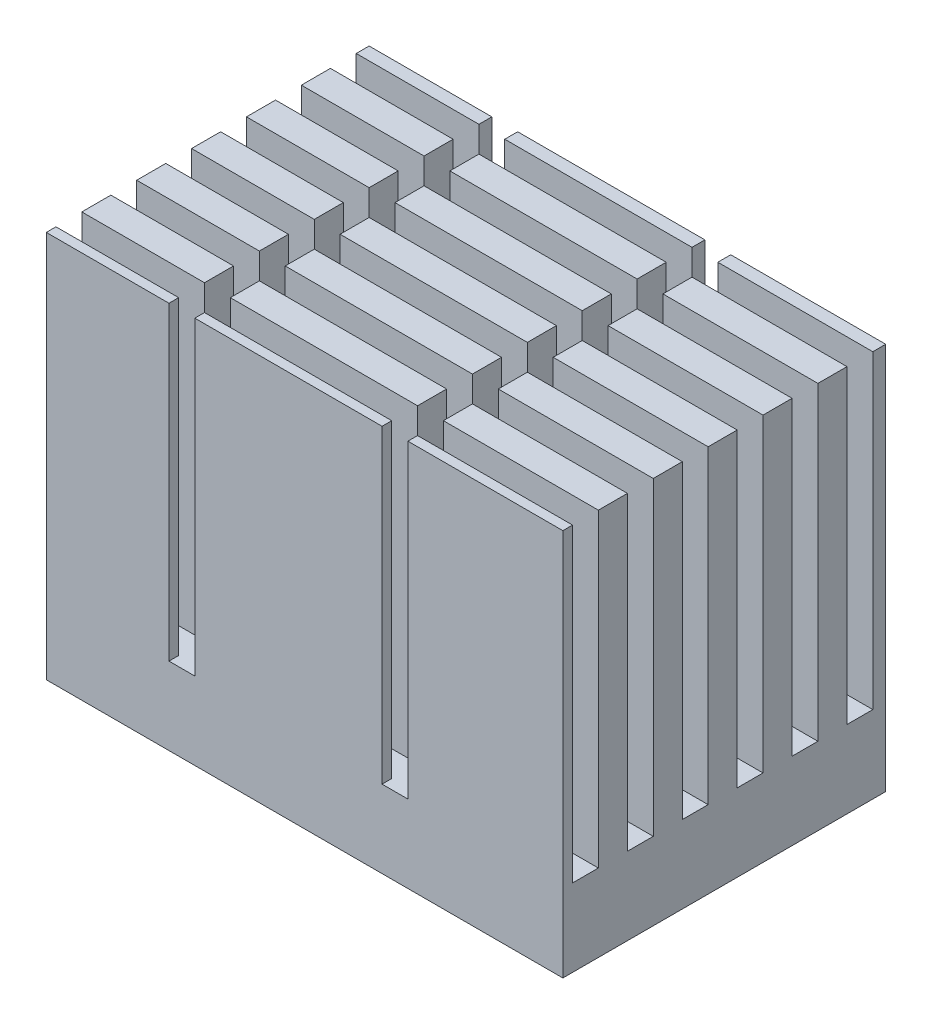
SolidWorks part; units mm, degrees
ref_plane "前视基准面" through (0, 0, 0) normal (0, 0, 1) x (1, 0, 0)
ref_plane "上视基准面" through (0, 0, 0) normal (0, 1, 0) x (1, 0, 0)
ref_plane "右视基准面" through (0, 0, 0) normal (1, 0, 0) x (0, 0, -1)
sketch "草图1" plane through (0, 0, 0) normal (0, 1, 0) x (1, 0, 0)
  line L0 (0, 37.5709) -> (0, -51.0007) construction
  line L1 (-20, 12.5) -> (20, 12.5)
  line L2 (-20, 12.5) -> (-20, -12.5)
  line L3 (-20, -12.5) -> (20, -12.5)
  line L4 (20, 12.5) -> (20, -12.5)
  line L5 (-48.656, 0) -> (59.7607, 0) construction
  dimension "D1" = 40
  dimension "D2" = 25
extrude "拉伸1" add sketch "草图1" along normal blind 30
sketch "草图2" plane through (0, 30, 0) normal (0, 1, 0) x (-1, 0, 0)
  line L0 (-20, 12.5) -> (-20, -12.5) construction
  line L1 (-20, -11.5) -> (20, -11.5)
  line L2 (-20, -11.5) -> (-20, -9.5)
  line L3 (-20, -9.5) -> (20, -9.5)
  line L4 (20, -11.5) -> (20, -9.5)
  line L5 (20, -12.5) -> (20, 12.5) construction
  line L6 (-20, -12.5) -> (20, -12.5) construction
  line L7 (-20, -7.25) -> (20, -7.25)
  line L8 (-20, -7.25) -> (-20, -5.25)
  line L9 (-20, -5.25) -> (20, -5.25)
  line L10 (20, -7.25) -> (20, -5.25)
  line L11 (-20, -3) -> (20, -3)
  line L12 (-20, -3) -> (-20, -1)
  line L13 (-20, -1) -> (20, -1)
  line L14 (20, -3) -> (20, -1)
  line L15 (-20, 1.25) -> (20, 1.25)
  line L16 (-20, 1.25) -> (-20, 3.25)
  line L17 (-20, 3.25) -> (20, 3.25)
  line L18 (20, 1.25) -> (20, 3.25)
  line L19 (-20, 5.5) -> (20, 5.5)
  line L20 (-20, 5.5) -> (-20, 7.5)
  line L21 (-20, 7.5) -> (20, 7.5)
  line L22 (20, 5.5) -> (20, 7.5)
  line L23 (-20, 9.75) -> (20, 9.75)
  line L24 (-20, 9.75) -> (-20, 11.75)
  line L25 (-20, 11.75) -> (20, 11.75)
  line L26 (20, 9.75) -> (20, 11.75)
  dimension "D1" = 2
  dimension "D2" = 1
extrude "切除-拉伸1" cut sketch "草图2" against normal offset from surface (24 mm away) 6 up to face at (0, 0, 0)
sketch "草图3" plane through (0, 30, 0) normal (0, 1, 0) x (-1, 0, 0)
  line L0 (-20, 12.5) -> (20, 12.5) construction
  line L1 (-8, 12.5) -> (-6, 12.5)
  line L2 (-8, 12.5) -> (-8, -12.5)
  line L3 (-8, -12.5) -> (-6, -12.5)
  line L4 (-6, 12.5) -> (-6, -12.5)
  line L5 (-20, -12.5) -> (20, -12.5) construction
  line L6 (-20, -11.5) -> (-20, -9.5) construction
  line L7 (8.5, 12.5) -> (10.5, 12.5)
  line L8 (8.5, 12.5) -> (8.5, -12.5)
  line L9 (8.5, -12.5) -> (10.5, -12.5)
  line L10 (10.5, 12.5) -> (10.5, -12.5)
  dimension "D1" = 12
  dimension "D2" = 2
extrude "切除-拉伸2" cut sketch "草图3" against normal up to surface (24 mm away) up to face at (0, 6, 6.5)
sketch "草图4" plane through (0, 0, 0) normal (0, -1, 0) x (1, 0, 0)
  line L0 (33.2472, 0) -> (-34.7303, 0) construction
  line L1 (0, 13.5955) -> (0, -13.5955) construction
  line L2 (16, 10.9864) -> (16, -11.9217) construction
  line L3 (-16, 10.9864) -> (-16, -11.9217) construction
  line L4 (-33.2472, 0) -> (34.7303, 0) construction
  circle A0 centre (16, 0) radius 1
  circle A1 centre (-16, 0) radius 1
  dimension "D1" = 2
  dimension "D2" = 32
extrude "切除-拉伸3" cut sketch "草图4" against normal blind 3
